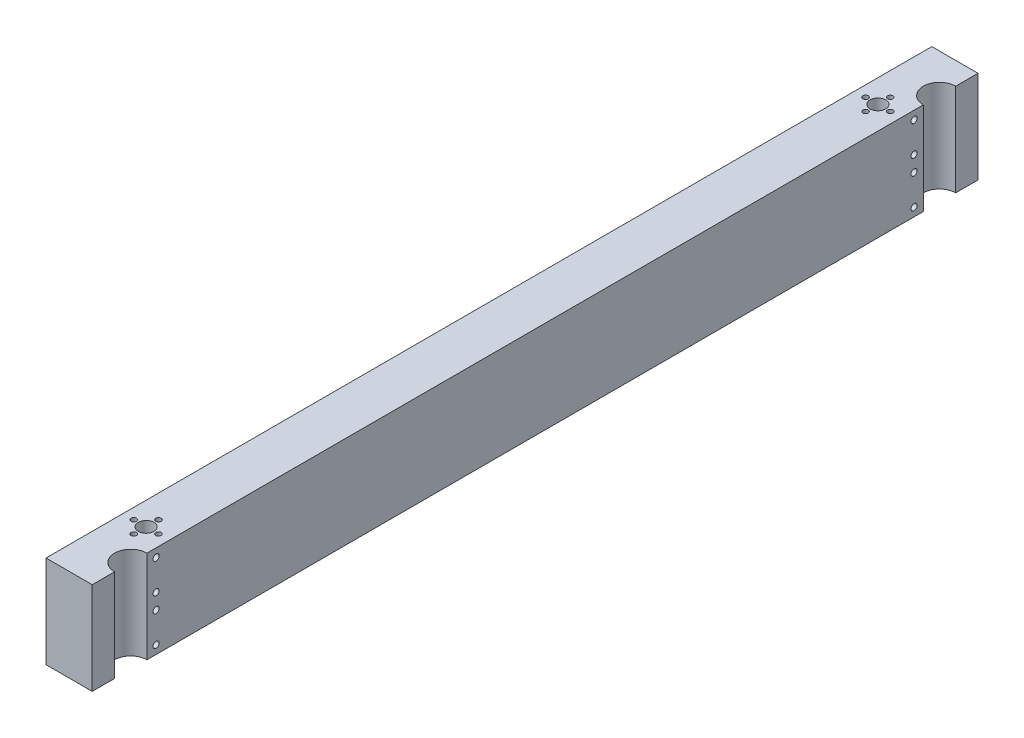
SolidWorks part; units mm, degrees
ref_plane "Front Plane" through (0, 0, 0) normal (0, 0, 1) x (1, 0, 0)
ref_plane "Top Plane" through (0, 0, 0) normal (0, 1, 0) x (1, 0, 0)
ref_plane "Right Plane" through (0, 0, 0) normal (1, 0, 0) x (0, 0, -1)
sketch "Sketch1" plane through (0, 0, 0) normal (0, 0, 1) x (1, 0, 0)
  line L1 (-15, -30) -> (15, -30)
  line L2 (-15, -30) -> (-15, 30)
  line L3 (-15, 30) -> (15, 30)
  line L4 (15, -30) -> (15, 30)
  line L5 (-15, -30) -> (15, 30) construction
  line L6 (-15, 30) -> (15, -30) construction
  point P0 (0, 0)
  dimension "D1" = 60
  dimension "D2" = 30
extrude "Boss-Extrude1" add sketch "Sketch1" along normal mid plane 575
sketch "Sketch2" plane through (0, 30, 0) normal (0, 1, 0) x (1, 0, 0)
  line L0 (0, -287.5) -> (0, -262.5) construction
  line L1 (15, -287.5) -> (-15, -287.5) construction
  line L2 (0, -262.5) -> (15, -262.5) construction
  circle A0 centre (15, -262.5) radius 10.5
  dimension "D3" = 21
  dimension "D1" = 25
  dimension "D2" = 15
extrude "Cut-Extrude1" cut sketch "Sketch2" against normal through all
sketch "Sketch3" plane through (0, 30, 0) normal (0, 1, 0) x (1, 0, 0)
  line L0 (0, -287.5) -> (0, -237.5) construction
  line L1 (15, -287.5) -> (-15, -287.5) construction
  circle A0 centre (0, -237.5) radius 5.1
  dimension "D2" = 10.2
  dimension "D1" = 50
extrude "Cut-Extrude2" cut sketch "Sketch3" against normal blind 10
mirror "Mirror2" about plane through (0, 0, 0) normal (0, 1, 0) of "Cut-Extrude2"
sketch "Sketch4" plane through (0, 30, 0) normal (0, 1, 0) x (1, 0, 0)
  line L0 (0, -237.5) -> (-8, -237.5) construction
  circle A0 centre (0, -237.5) radius 4
  circle A1 centre (-8, -237.5) radius 1.75
  circle A2 centre (0, -229.5) radius 1.75
  circle A3 centre (8, -237.5) radius 1.75
  circle A4 centre (0, -245.5) radius 1.75
  point P5 (0, -237.5)
  point P14 (0, -237.5)
  dimension "D1" = 3.5
  dimension "D2" = 8
  dimension "D4" = 16
  dimension "D3" = 4
extrude "Cut-Extrude3" cut sketch "Sketch4" against normal through all
sketch "Sketch5" plane through (15, 0, 0) normal (1, 0, 0) x (0, 0, -1)
  line L0 (-246, 30) -> (-246, -30) construction
  line L1 (-252, 30) -> (287.5, 30) construction
  line L2 (-252, -30) -> (287.5, -30) construction
  line L3 (-287.5, -30) -> (-287.5, 30) construction
  line L4 (-287.5, 0) -> (287.5, 0) construction
  line L5 (287.5, -30) -> (287.5, 30) construction
  line L6 (-252, 30) -> (-252, -30) construction
  circle A0 centre (-246, 24.5) radius 2
  circle A1 centre (-246, 5) radius 2
  circle A2 centre (-246, -5) radius 2
  circle A3 centre (-246, -24.5) radius 2
  dimension "D2" = 4
  dimension "D3" = 4
  dimension "D4" = 10
  dimension "D5" = 49
  dimension "D1" = 6
extrude "Cut-Extrude4" cut sketch "Sketch5" against normal blind 7
mirror "Mirror1" about plane through (0, 0, 0) normal (0, 0, 1) of "Cut-Extrude4", "Cut-Extrude1", "Cut-Extrude2", "Mirror2", "Cut-Extrude3"
